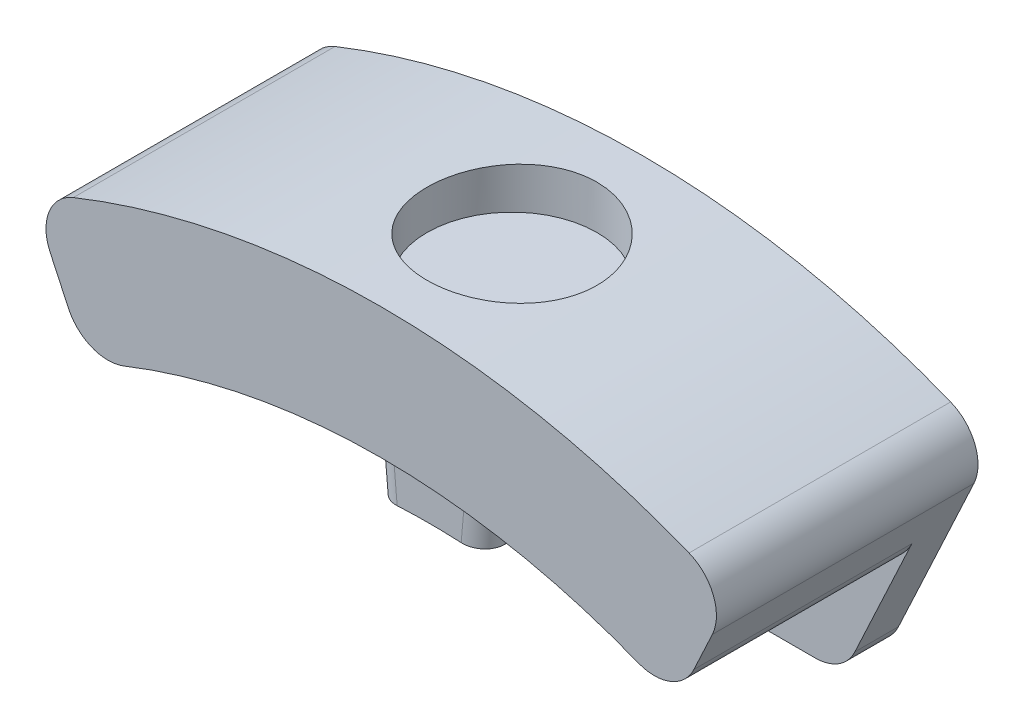
SolidWorks part; units mm, degrees
ref_plane "前视基准面" through (0, 0, 0) normal (0, 0, 1) x (1, 0, 0)
ref_plane "上视基准面" through (0, 0, 0) normal (0, 1, 0) x (1, 0, 0)
ref_plane "右视基准面" through (0, 0, 0) normal (1, 0, 0) x (0, 0, -1)
sketch "草图1" plane through (0, 0, 0) normal (0, 0, 1) x (1, 0, 0)
  line L0 (-8.0297, 17.2198) -> (0, 0) construction
  line L1 (0, 0) -> (8.0297, 17.2198) construction
  line L2 (-8.0297, 17.2198) -> (-6.7619, 14.5009)
  line L3 (8.0297, 17.2198) -> (6.7619, 14.5009)
  arc A0 (-6.7619, 14.5009) -> (6.7619, 14.5009) centre (0, 0) cw
  arc A1 (-8.0297, 17.2198) -> (8.0297, 17.2198) centre (0, 0) cw
  dimension "D2" = 16
  dimension "D3" = 19
  dimension "D1" = 50
extrude "凸台-拉伸1" add sketch "草图1" along normal blind 5
sketch "草图2" plane through (0, 0, 0) normal (1, 0, 0) x (0, 0, -1)
  line L0 (0, 17.2198) -> (0, 14.5009) construction
  line L1 (-3.9, 17.85) -> (-2.1, 17.85)
  line L2 (-3.9, 17.85) -> (-3.9, 14.15)
  line L3 (-3.9, 14.15) -> (-2.1, 14.15)
  line L4 (-2.1, 17.85) -> (-2.1, 14.15)
  line L5 (-3.9, 17.85) -> (-2.1, 14.15) construction
  line L6 (-3.9, 14.15) -> (-2.1, 17.85) construction
  point P0 (-3, 16)
  dimension "D1" = 16
  dimension "D2" = 3
  dimension "D3" = 3.7
  dimension "D4" = 1.8
revolve "旋转1" add sketch "草图2" angle 5 about axis through (0, 0, 5) along (0, 0, -1)
mirror "镜向1" about plane through (0, 0, 0) normal (1, 0, 0) of "旋转1"
fillet "圆角1" radius 0.5 4 edges at (1.3139, 15.0176, 2.1) (1.3139, 15.0176, 3.9) (-1.3139, 15.0176, 2.1) (-1.3139, 15.0176, 3.9)
fillet "圆角2" radius 1 2 edges at (-6.7619, 14.5009, 2.5) (6.7619, 14.5009, 2.5)
fillet "圆角3" radius 1 2 edges at (-8.0297, 17.2198, 2.5) (8.0297, 17.2198, 2.5)
sketch "草图3" plane through (0, 0, 0) normal (0, 1, 0) x (1, 0, 0)
  line L0 (0, -5) -> (0, 0) construction
  line L1 (7.0607, 0) -> (-7.0607, 0) construction
  circle A0 centre (0, -3) radius 2.25
  dimension "D1" = 4.5
  dimension "D2" = 3
sketch "草图4" plane through (0, 0, 0) normal (0, 0, -1) x (-1, 0, 0)
  line L1 (-2, 20) -> (2, 20)
  line L2 (-2, 20) -> (-2, 18)
  line L3 (-2, 18) -> (2, 18)
  line L4 (2, 20) -> (2, 18)
  line L5 (-2, 20) -> (2, 18) construction
  line L6 (-2, 18) -> (2, 20) construction
  arc A0 (7.0607, 17.6394) -> (-7.0607, 17.6394) centre (0, 0) ccw construction
  point P0 (0, 19)
  dimension "D1" = 4
  dimension "D2" = 2
extrude "切除-拉伸1" cut sketch "草图4" against normal blind 4
fillet "圆角4" [suppressed] radius 2
sketch "草图5" plane through (0, 18, 0) normal (0, 1, 0) x (1, 0, 0)
  line L0 (0, -5) -> (0, 0) construction
  line L1 (7.0607, 0) -> (2, 0) construction
  line L3 (2, -4) -> (-2, -4)
  line L4 (2, -4) -> (2, 0)
  line L5 (2, 0) -> (-2, 0)
  line L6 (-2, -4) -> (-2, 0)
  line L7 (2, -4) -> (-2, 0) construction
  line L8 (2, 0) -> (-2, -4) construction
  circle A0 centre (0, -2) radius 1.95
  dimension "D1" = 3.9
  dimension "D2" = 2
extrude "凸台-拉伸5" add sketch "草图5" along normal up to surface (1 mm away)
sketch "草图6" plane through (0, 0, 0) normal (0, 0, -1) x (-1, 0, 0)
  line L0 (-7.5954, 16.2883) -> (-5.5957, 12)
  line L1 (-5.5957, 12) -> (5.5957, 12)
  line L2 (5.5957, 12) -> (7.5954, 16.2883)
  line L3 (7.5954, 16.2883) -> (7.1721, 15.3806) construction
  line L4 (-7.1721, 15.3806) -> (-7.5954, 16.2883) construction
  arc A0 (7.5954, 16.2883) -> (7.0607, 17.6394) centre (6.6891, 16.711) ccw construction
  arc A1 (7.0607, 17.6394) -> (-7.0607, 17.6394) centre (0, 0) ccw construction
  arc A2 (-7.0607, 17.6394) -> (-7.5954, 16.2883) centre (-6.6891, 16.711) ccw construction
  arc A3 (7.5954, 16.2883) -> (7.0607, 17.6394) centre (6.6891, 16.711) ccw
  arc A4 (7.0607, 17.6394) -> (-7.0607, 17.6394) centre (0, 0) ccw
  arc A5 (-7.0607, 17.6394) -> (-7.5954, 16.2883) centre (-6.6891, 16.711) ccw
  dimension "D1" = 12
extrude "凸台-拉伸6" add sketch "草图6" along normal blind 1
fillet "圆角5" radius 1 2 edges at (-5.5957, 12, -0.5) (5.5957, 12, -0.5)
